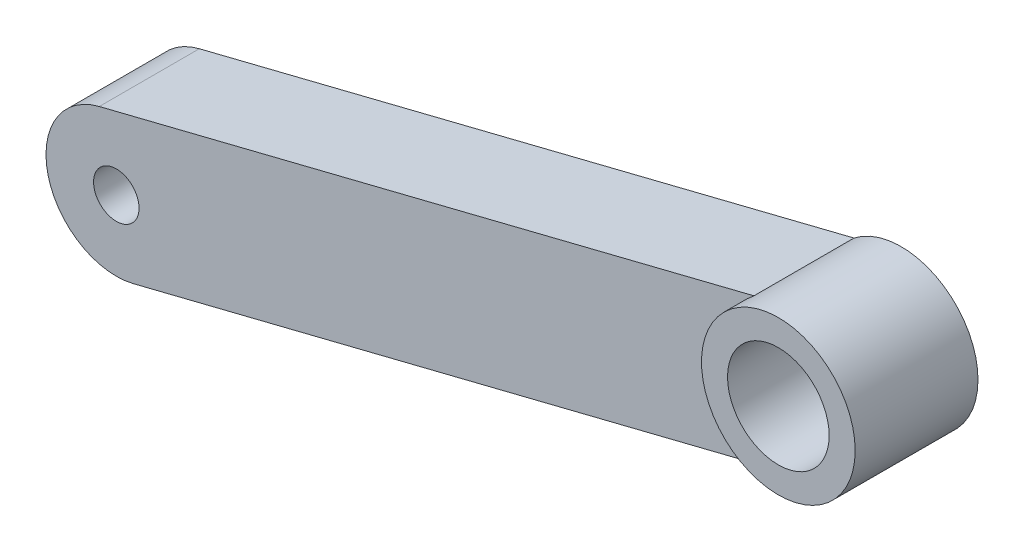
SolidWorks part; units mm, degrees
ref_plane "Front Plane" through (0, 0, 0) normal (0, 0, 1) x (1, 0, 0)
ref_plane "Top Plane" through (0, 0, 0) normal (0, 1, 0) x (1, 0, 0)
ref_plane "Right Plane" through (0, 0, 0) normal (1, 0, 0) x (0, 0, -1)
ref_plane "Plane1" through (0, 0, 6.35) normal (0, 0, 1) x (1, 0, 0)
sketch "Sketch3" plane through (0, 0, 6.35) normal (0, 0, 1) x (1, 0, 0)
  line L0 (-1.0999, -54.61) -> (-15.7313, -54.61) construction
  line L1 (-8.89, -27.432) -> (-34.557, -27.432) construction
  line L2 (-8.89, -27.432) -> (-76.6611, -44.3466) construction
  line L3 (-7.62, -54.61) -> (-64.9771, -68.9254) construction
  line L4 (-6.1942, -60.3228) -> (-63.5513, -74.6382)
  line L5 (-9.0458, -48.8972) -> (-66.4029, -63.2126)
  circle A0 centre (-7.62, -54.61) radius 4.2545
  circle A3 centre (-76.6671, -71.3707) radius 1.905 construction
  circle A4 centre (-88.4241, -48.0538) radius 1.905 construction
  arc A5 (-6.1942, -60.3228) -> (-9.0458, -48.8972) centre (-7.62, -54.61) ccw
  arc A6 (-66.4029, -63.2126) -> (-63.5513, -74.6382) centre (-64.9771, -68.9254) ccw
  circle A7 centre (-64.9771, -68.9254) radius 1.905
  point P16 (-36.2985, -61.7677)
  dimension "D1" = 8.509
  dimension "D3" = 3.81
  dimension "D2" = 11.757
  dimension "D4" = 11.684
extrude "Boss-Extrude1" add sketch "Sketch3" along normal mid plane 8.382
sketch "Sketch4" plane through (0, 0, 6.35) normal (0, 0, 1) x (1, 0, 0)
  circle A0 centre (-7.62, -54.61) radius 4.2545
  circle A1 centre (-7.62, -54.61) radius 6.4362
  dimension "D1" = 8.509
extrude "Boss-Extrude2" add sketch "Sketch4" along normal mid plane 12.192
sketch "Sketch6" plane through (0, 0, 2.159) normal (0, 0, -1) x (-1, 0, 0)
  circle A0 centre (7.62, -54.61) radius 6.4362
extrude "Cut-Extrude1" cut sketch "Sketch6" along normal up to surface (1.905 mm away) up to face at (-1.1838, -54.61, 0.254)
